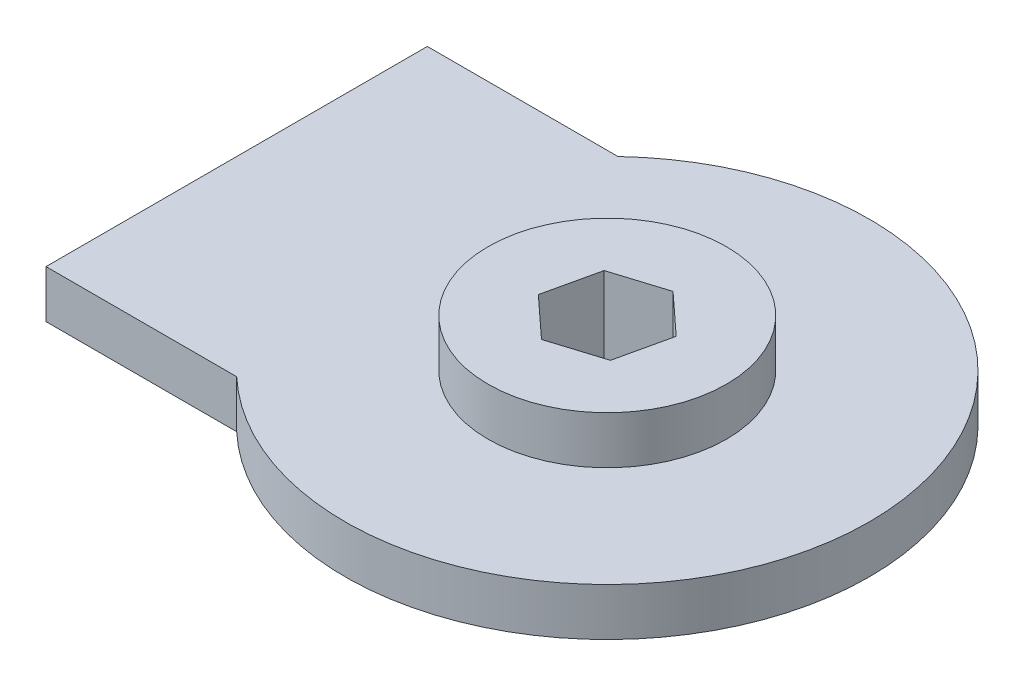
SolidWorks part; units mm, degrees
ref_plane "Front" through (0, 0, 0) normal (0, 0, 1) x (1, 0, 0)
ref_plane "Top" through (0, 0, 0) normal (0, 1, 0) x (1, 0, 0)
ref_plane "Right" through (0, 0, 0) normal (1, 0, 0) x (0, 0, -1)
sketch "Sketch1" plane through (0, 0, 0) normal (0, 1, 0) x (1, 0, 0)
  line L0 (-49.3707, 0) -> (0, 0) construction
  line L7 (-23.9707, 25.4) -> (-49.3707, 25.4)
  line L8 (-23.9707, 25.4) -> (-23.9707, -25.4)
  line L9 (-23.9707, -25.4) -> (-49.3707, -25.4)
  line L10 (-49.3707, 25.4) -> (-49.3707, -25.4)
  circle A0 centre (0, 0) radius 34.925
  dimension "D2" = 69.85
  dimension "D3" = 50.8
  dimension "D4" = 25.4
extrude "Boss-Extrude1" add sketch "Sketch1" along normal blind 6.35
sketch "Sketch2" plane through (0, 6.35, 0) normal (0, 1, 0) x (1, 0, 0)
  circle A0 centre (0, 0) radius 15.875
  dimension "D1" = 31.75
extrude "Boss-Extrude2" add sketch "Sketch2" along normal blind 6.35
sketch "Sketch3" plane through (0, 12.7, 0) normal (0, 1, 0) x (1, 0, 0)
  line L1 (5.3912, -4.9697) -> (6.9995, 2.1841)
  line L2 (6.9995, 2.1841) -> (1.6083, 7.1538)
  line L3 (1.6083, 7.1538) -> (-5.3912, 4.9697)
  line L4 (-5.3912, 4.9697) -> (-6.9995, -2.1841)
  line L5 (-6.9995, -2.1841) -> (-1.6083, -7.1538)
  line L6 (-1.6083, -7.1538) -> (5.3912, -4.9697)
  circle A0 centre (0, 0) radius 6.35 construction
  dimension "D1" = 12.7
extrude "Cut-Extrude1" cut sketch "Sketch3" against normal through all
